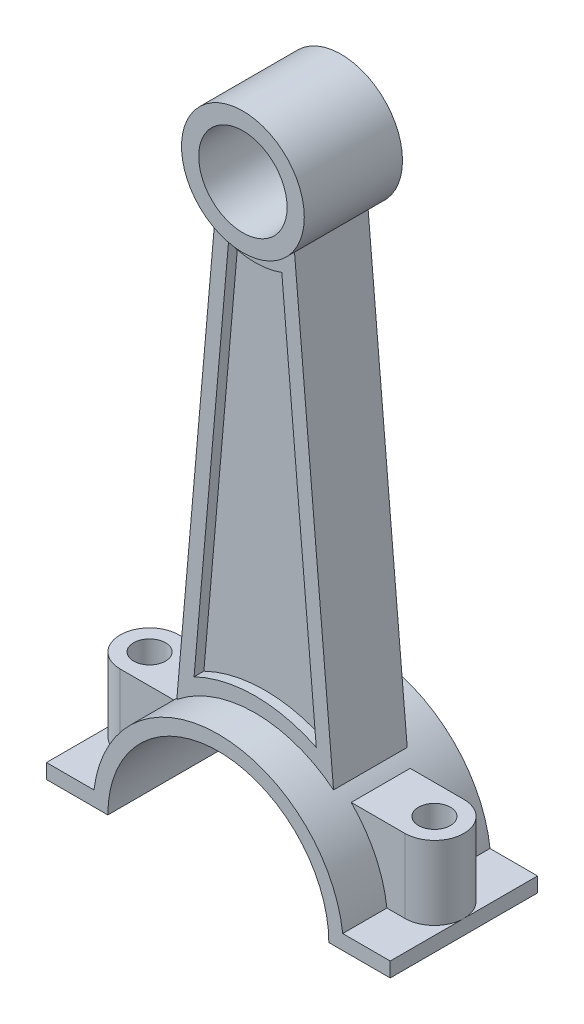
SolidWorks part; units mm, degrees
ref_plane "Front Plane" through (0, 0, 0) normal (0, 0, 1) x (1, 0, 0)
ref_plane "Top Plane" through (0, 0, 0) normal (0, 1, 0) x (1, 0, 0)
ref_plane "Right Plane" through (0, 0, 0) normal (1, 0, 0) x (0, 0, -1)
sketch "Sketch1" plane through (0, 0, 0) normal (0, 0, 1) x (1, 0, 0)
  line L0 (-22.5, 0) -> (-35, 0)
  line L1 (-35, 0) -> (-35, 3)
  line L2 (-35, 3) -> (-25.3229, 3)
  line L3 (22.5, 0) -> (35, 0)
  line L4 (35, 0) -> (35, 3)
  line L5 (35, 3) -> (25.3229, 3)
  arc A0 (-25.3229, 3) -> (25.3229, 3) centre (0, 0) cw
  arc A1 (-22.5, 0) -> (22.5, 0) centre (0, 0) cw
  dimension "D1" = 22.5
  dimension "D2" = 3
  dimension "D3" = 35
  dimension "D4" = 3
  dimension "D5" = 3
  dimension "D6" = 35
extrude "Boss-Extrude1" add sketch "Sketch1" along normal mid plane 30
ref_plane "Plane1" through (0, 18, 0) normal (0, 1, 0) x (1, 0, 0)
sketch "Sketch3" plane through (0, 18, 0) normal (0, 1, 0) x (1, 0, 0)
  line L0 (-18.06, 6) -> (-18.06, -6)
  line L1 (-18.06, -6) -> (-29, -6)
  line L2 (-18.06, 6) -> (-29, 6)
  line L3 (-35, -15) -> (-35, 15) construction
  arc A0 (-29, 6) -> (-29, -6) centre (-29, 0) ccw
  point P2 (-18.06, 0)
  dimension "D2" = 6
  dimension "D1" = 12
  dimension "D3" = 10.94
extrude "Boss-Extrude2" add sketch "Sketch3" against normal up to next
sketch "Sketch4" plane through (0, 18, 0) normal (0, 1, 0) x (1, 0, 0)
  circle A0 centre (-29, 0) radius 3.25
  dimension "D1" = 6.5
extrude "Cut-Extrude1" cut sketch "Sketch4" against normal through all
mirror "Mirror1" about plane through (0, 0, 0) normal (1, 0, 0) of "Cut-Extrude1", "Boss-Extrude2"
sketch "Sketch6" plane through (0, 0, 0) normal (0, 0, 1) x (1, 0, 0)
  line L0 (15.9574, 19.89) -> (8.0038, 110.8)
  line L1 (-15.9574, 19.89) -> (-8.0038, 110.8)
  line L2 (29, 18) -> (18.0624, 18) construction
  line L3 (-29, 18) -> (-18.0624, 18) construction
  line L4 (-35, 0) -> (-22.5, 0) construction
  line L5 (22.5, 0) -> (35, 0) construction
  arc A0 (25.3229, 3) -> (-25.3229, 3) centre (0, 0) ccw construction
  arc A1 (15.9574, 19.89) -> (-15.9574, 19.89) centre (0, 0) ccw
  arc A3 (8.0038, 110.8) -> (-8.0038, 110.8) centre (0, 120.4015) cw
  point P15 (16.2241, 19.673)
  dimension "D1" = 95
  dimension "D3" = 12.5
  dimension "D2" = 95
  dimension "D4" = 110.8
  dimension "D5" = 19.89
  dimension "D6" = 19.89
extrude "Boss-Extrude3" add sketch "Sketch6" along normal mid plane 15
sketch "Sketch7" plane through (0, 0, 7.5) normal (0, 0, 1) x (1, 0, 0)
  line L15 (-5.4227, 105.881) -> (-12.4428, 25.6403)
  line L16 (12.4428, 25.6403) -> (5.4227, 105.881)
  line L17 (-5.4227, 105.881) -> (-12.4428, 25.6403)
  line L18 (12.4428, 25.6403) -> (5.4227, 105.881)
  arc A18 (12.4428, 25.6403) -> (-12.4428, 25.6403) centre (0, 0) ccw
  arc A19 (-5.4227, 105.881) -> (5.4227, 105.881) centre (0, 120.4015) ccw
  arc A20 (12.4428, 25.6403) -> (-12.4428, 25.6403) centre (0, 0) ccw
  arc A21 (-5.4227, 105.881) -> (5.4227, 105.881) centre (0, 120.4015) ccw
  dimension "D1" = 3
extrude "Cut-Extrude2" cut sketch "Sketch7" against normal blind 2
mirror "Mirror2" about plane through (0, 0, 0) normal (0, 0, 1) of "Cut-Extrude2"
sketch "Sketch9" plane through (0, 0, 0) normal (0, 0, 1) x (1, 0, 0)
  circle A0 centre (0, 120.4015) radius 12.5
  arc A3 (-8.0038, 110.8) -> (8.0038, 110.8) centre (0, 120.4015) ccw construction
  circle A4 centre (0, 120.4015) radius 9
  dimension "D1" = 25
  dimension "D2" = 18
extrude "Boss-Extrude4" add sketch "Sketch9" along normal mid plane 20
